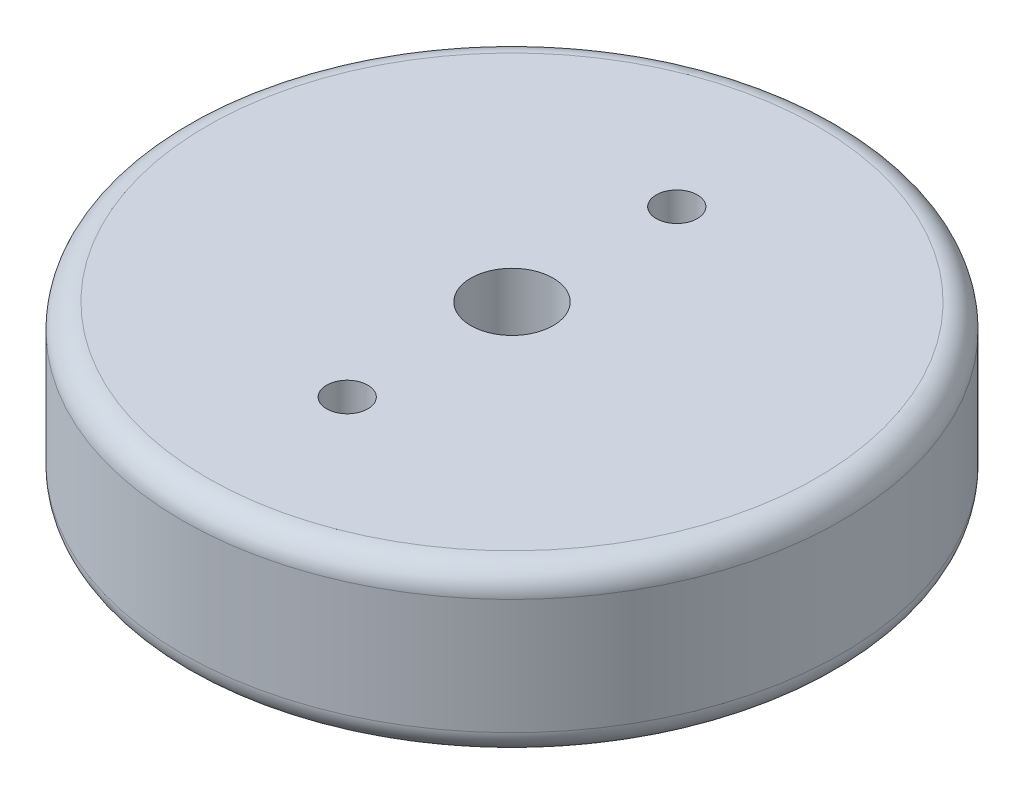
SolidWorks part; units mm, degrees
ref_plane "前基準面" through (0, 0, 0) normal (0, 0, 1) x (1, 0, 0)
ref_plane "上基準面" through (0, 0, 0) normal (0, 1, 0) x (1, 0, 0)
ref_plane "右基準面" through (0, 0, 0) normal (1, 0, 0) x (0, 0, -1)
sketch "草圖1" plane through (0, 0, 0) normal (0, 1, 0) x (1, 0, 0)
  circle A0 centre (0, 0) radius 40
  circle A1 centre (0, 0) radius 5
  dimension "D1" = 80
  dimension "D2" = 10
extrude "填料-伸長1" add sketch "草圖1" along normal blind 20
fillet "圓角1" radius 3 2 edges at (0, 0, 40) (0, 20, 40)
sketch "草圖2" plane through (0, 20, 0) normal (0, 1, 0) x (1, 0, 0)
  line L0 (0, 36.3239) -> (0, -37) construction
  circle A0 centre (0, 0) radius 37 construction
  circle A1 centre (0, 20) radius 2.5
  circle A2 centre (0, -20) radius 2.5
  dimension "D1" = 20
  dimension "D3" = 5
  dimension "D2" = 20
extrude "除料-伸長1" cut sketch "草圖2" against normal through all
